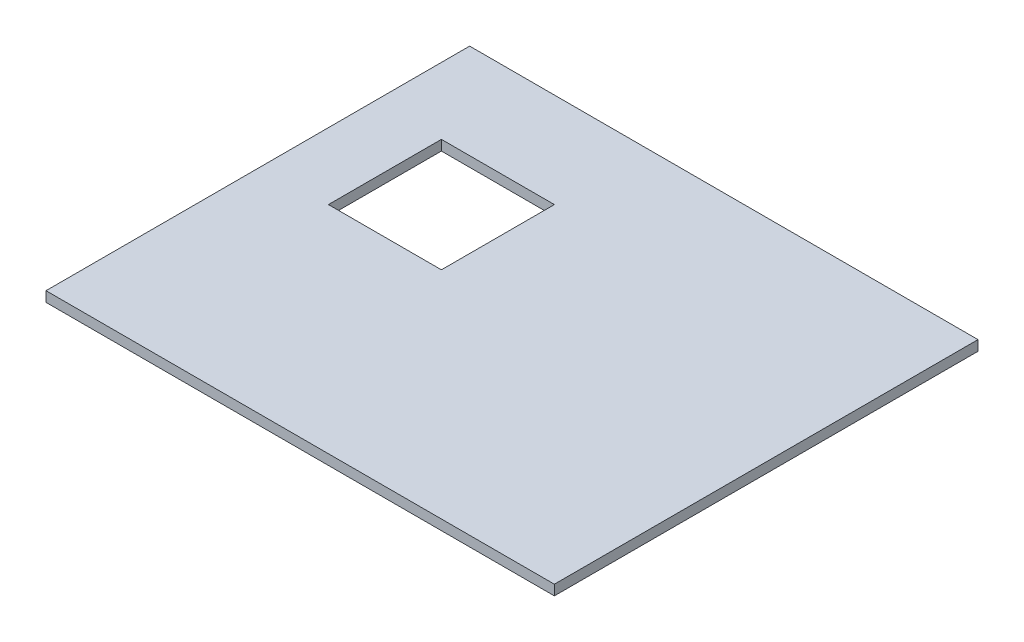
SolidWorks part; units mm, degrees
ref_plane "Front Plane" through (0, 0, 0) normal (0, 0, 1) x (1, 0, 0)
ref_plane "Top Plane" through (0, 0, 0) normal (0, 1, 0) x (1, 0, 0)
ref_plane "Right Plane" through (0, 0, 0) normal (1, 0, 0) x (0, 0, -1)
sketch "Sketch1" plane through (0, 0, 0) normal (0, 1, 0) x (1, 0, 0)
  line L1 (-457.2, -381) -> (457.2, -381)
  line L2 (-457.2, -381) -> (-457.2, 381)
  line L3 (-457.2, 381) -> (457.2, 381)
  line L4 (457.2, -381) -> (457.2, 381)
  line L5 (-457.2, -381) -> (457.2, 381) construction
  line L6 (-457.2, 381) -> (457.2, -381) construction
  line L7 (-337.312, 210.3438) -> (-134.112, 210.3438)
  line L8 (-337.312, 210.3438) -> (-337.312, 7.1437)
  line L9 (-337.312, 7.1437) -> (-134.112, 7.1437)
  line L10 (-134.112, 210.3438) -> (-134.112, 7.1437)
  line L11 (-337.312, 210.3438) -> (-134.112, 7.1437) construction
  line L12 (-337.312, 7.1437) -> (-134.112, 210.3438) construction
  point P0 (0, 0)
  point P6 (-235.712, 108.7438)
  dimension "D1" = 762
  dimension "D2" = 914.4
  dimension "D3" = 221.488
  dimension "D4" = 272.2562
extrude "Boss-Extrude1" add sketch "Sketch1" along normal blind 18.2562
